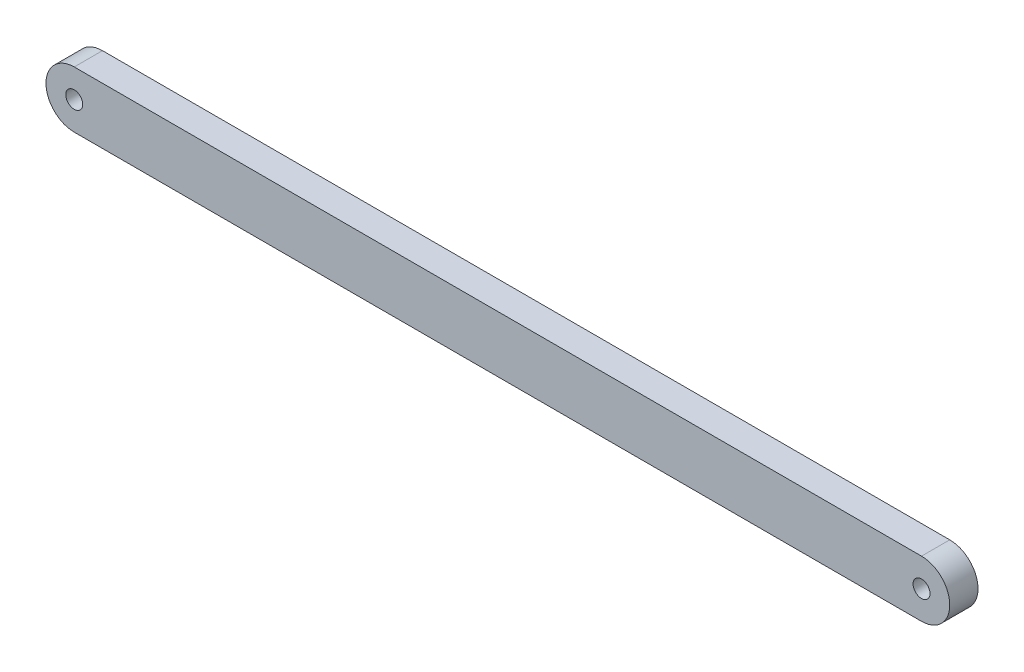
SolidWorks part; units mm, degrees
ref_plane "Plan de face" through (0, 0, 0) normal (0, 0, 1) x (1, 0, 0)
ref_plane "Plan de dessus" through (0, 0, 0) normal (0, 1, 0) x (1, 0, 0)
ref_plane "Plan de droite" through (0, 0, 0) normal (1, 0, 0) x (0, 0, -1)
sketch "Esquisse1" plane through (0, 0, 0) normal (0, 0, 1) x (1, 0, 0)
  line L0 (-75, 0) -> (75, 0) construction
  line L1 (-75, 5) -> (75, 5)
  line L2 (-75, -5) -> (75, -5)
  arc A0 (-75, 5) -> (-75, -5) centre (-75, 0) ccw
  arc A1 (75, -5) -> (75, 5) centre (75, 0) ccw
  circle A2 centre (-75, 0) radius 1.5
  circle A3 centre (75, 0) radius 1.5
  point P2 (0, 0)
  dimension "D1" = 5
  dimension "D3" = 3
  dimension "D4" = 3
  dimension "D2" = 150
extrude "Boss.-Extru.1" add sketch "Esquisse1" along normal blind 5
